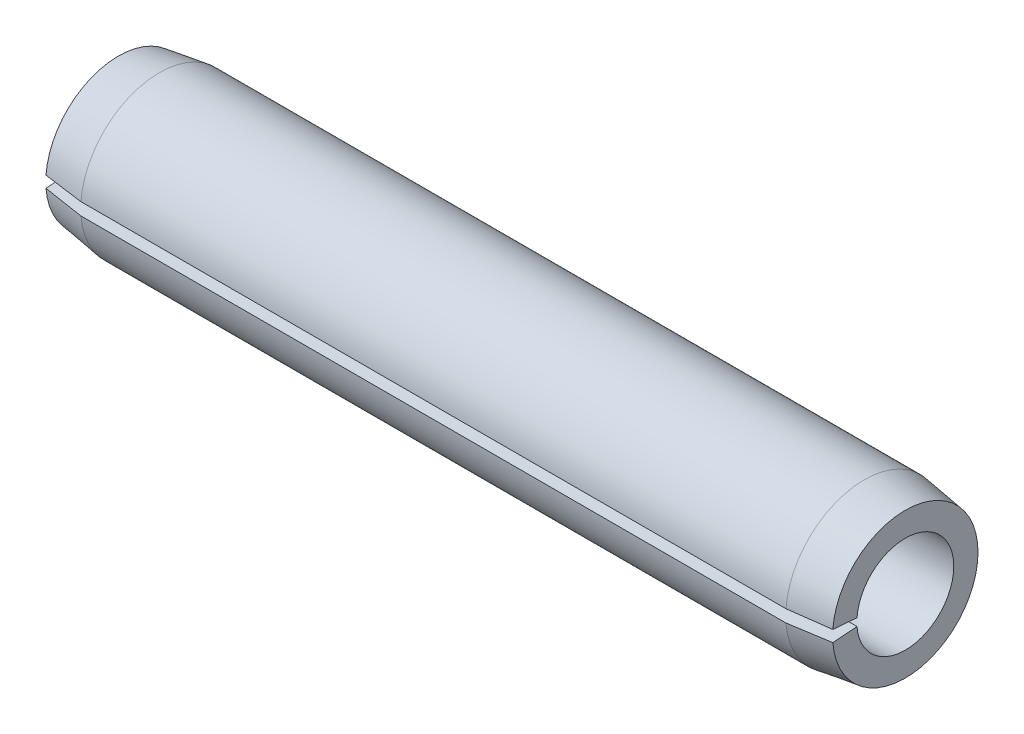
SolidWorks part; units mm, degrees
material "201 Annealed Stainless Steel (SS)"
ref_plane "Plane1" through (0, 0, 0) normal (0, 0, 1) x (1, 0, 0)
ref_plane "Plane2" through (0, 0, 0) normal (0, 1, 0) x (1, 0, 0)
ref_plane "Plane3" through (0, 0, 0) normal (1, 0, 0) x (0, 0, -1)
sketch "Sketch1" plane through (0, 0, 0) normal (0, 0, 1) x (1, 0, 0)
  line L0 (-9.525, 0) -> (111.125, 0) construction
  line L1 (0, 1.9558) -> (31.75, 1.9558)
  line L2 (31.75, 1.9558) -> (31.75, 2.9337)
  line L3 (31.75, 2.9337) -> (30.099, 3.175)
  line L4 (30.099, 3.175) -> (1.651, 3.175)
  line L5 (1.651, 3.175) -> (0, 2.9337)
  line L7 (0, 2.9337) -> (0, 1.9558)
  dimension "Diameter" = 6.35
  dimension "Length" = 31.75
  dimension "Thickness" = 1.2192
  dimension "Top_ch_len" = 1.651
  dimension "Bottom_ch_len" = 1.651
  dimension "Bottom_ch_dia" = 5.8674
  dimension "Top_ch_dia" = 5.8674
revolve "Base-Revolve" add sketch "Sketch1" angle 360 about L0
sketch "Sketch2" plane through (0, 0, 0) normal (-1, 0, 0) x (0, -1, 0)
  line L0 (0, 0) -> (0.2541, 3.2285)
  line L1 (0, -3.175) -> (0, 12.7) construction
  line L2 (0, 0) -> (-0.2541, 3.2285)
  arc A0 (0.2541, 3.2285) -> (-0.2541, 3.2285) centre (0, 0) ccw
  dimension "D1" = 3.2385
  dimension "Gap_ang" = 9
extrude "Gap" cut sketch "Sketch2" against normal through all
equation "\"D1@Sketch2\" = \"Diameter@Sketch1\" * 0.51"
equation "' \"Bottom_ch_dia@Sketch1\" = \"Diameter@Sketch1\" -  ( \"Thickness@Sketch1\" / 2 ) "
equation "' \"Top_ch_dia@Sketch1\" = \"Bottom_ch_dia@Sketch1\""
equation "' \"Top_ch_len@Sketch1\" = \"Bottom_ch_len@Sketch1\""
